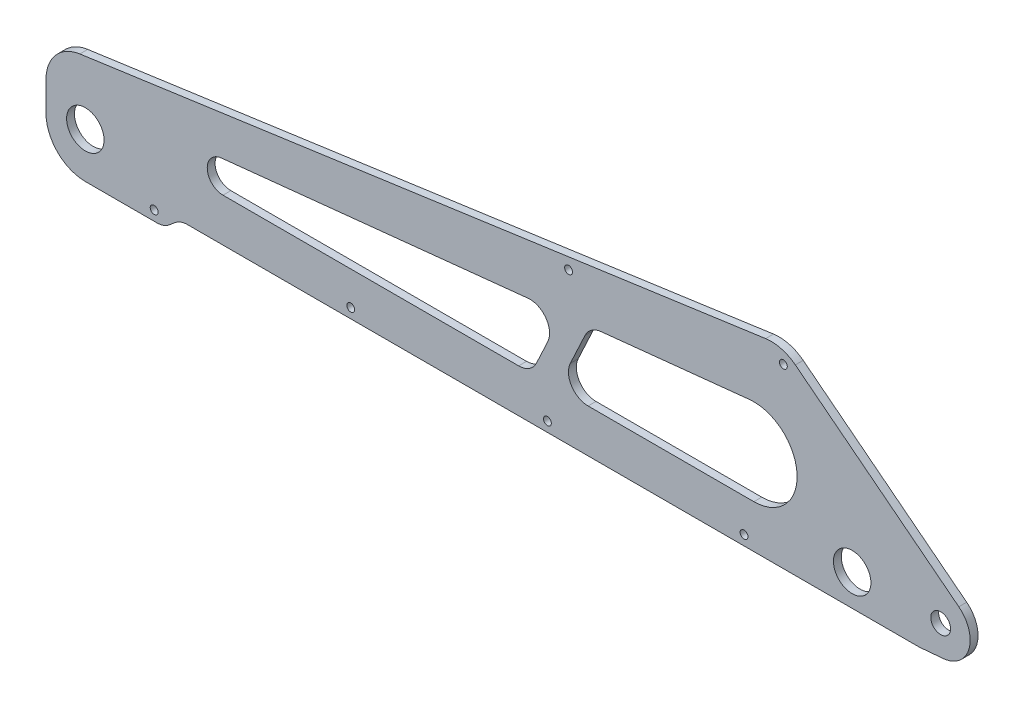
SolidWorks part; units mm, degrees
ref_plane "前视基准面" through (0, 0, 0) normal (0, 0, 1) x (1, 0, 0)
ref_plane "上视基准面" through (0, 0, 0) normal (0, 1, 0) x (1, 0, 0)
ref_plane "右视基准面" through (0, 0, 0) normal (1, 0, 0) x (0, 0, -1)
sketch "草图1" plane through (0, 0, 0) normal (0, 0, 1) x (1, 0, 0)
  line L0 (-134.3031, 6) -> (-50, 6)
  line L1 (-52.2754, 49.882) -> (-127.84, 42.0246)
  line L2 (-135.8688, 36.3044) -> (-143.3662, 20.2262)
  line L3 (-320, 6) -> (-169.6112, 6)
  line L4 (-160.5482, 11.7738) -> (-154.85, 23.9935)
  line L5 (-164.9474, 38.166) -> (-320.8274, 21.9571)
  line L6 (-392.7835, 31.8054) -> (-44.004, 80.8231)
  line L7 (-28.9073, 76.778) -> (54.2349, 11.8202)
  line L8 (-344.4459, -18.3396) -> (-347.2118, -20.6604)
  line L9 (-353.6397, -23) -> (-390, -23)
  line L10 (-410, -3) -> (-410, 12)
  line L11 (34.2249, -16) -> (-338.018, -16)
  line L12 (46.3073, -14.9429) -> (34.2249, -16)
  line L13 (-390, 0) -> (0, 0) construction
  line L14 (0, 0) -> (45, 0) construction
  circle A0 centre (45, 0) radius 5.03
  circle A1 centre (-55, -11) radius 2
  circle A2 centre (-144.2291, 61) radius 2
  circle A3 centre (0, 0) radius 9.53
  circle A4 centre (-255, -11) radius 2
  circle A5 centre (-390, 0) radius 9.53
  circle A6 centre (-35, 74) radius 2
  circle A7 centre (-355, -18) radius 2
  circle A8 centre (-155, -11) radius 2
  arc A9 (-50, 6) -> (-52.2754, 49.882) centre (-50, 28) ccw
  arc A10 (-127.84, 42.0246) -> (-135.8688, 36.3044) centre (-126.8058, 32.0782) ccw
  arc A11 (-143.3662, 20.2262) -> (-134.3031, 6) centre (-134.3031, 16) ccw
  arc A12 (-320.8274, 21.9571) -> (-320, 6) centre (-320, 14) ccw
  arc A13 (-169.6112, 6) -> (-160.5482, 11.7738) centre (-169.6112, 16) ccw
  arc A14 (-154.85, 23.9935) -> (-164.9474, 38.166) centre (-163.9131, 28.2196) ccw
  arc A15 (-392.7835, 31.8054) -> (-410, 12) centre (-390, 12) ccw
  arc A16 (-28.9073, 76.778) -> (-44.004, 80.8231) centre (-41.2205, 61.0178) ccw
  arc A17 (46.3073, -14.9429) -> (54.2349, 11.8202) centre (45, 0) ccw
  arc A18 (-338.018, -16) -> (-344.4459, -18.3396) centre (-338.018, -26) ccw
  arc A19 (-353.6397, -23) -> (-347.2118, -20.6604) centre (-353.6397, -13) ccw
  arc A20 (-410, -3) -> (-390, -23) centre (-390, -3) ccw
extrude "凸台-拉伸1" add sketch "草图1" along normal blind 4 contours L6 A16 L7 A17 L12 L11 A18 L8 A19 L9 A20 L10 A15
